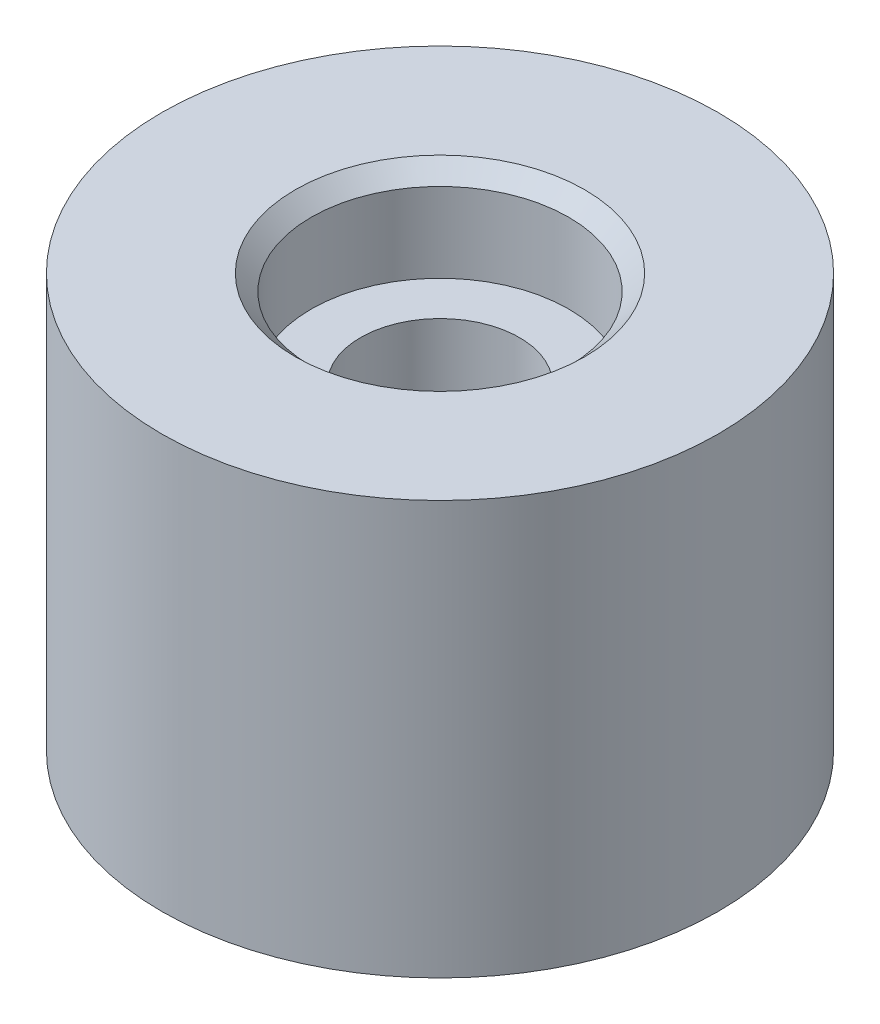
SolidWorks part; units mm, degrees
ref_plane "Front" through (0, 0, 0) normal (0, 0, 1) x (1, 0, 0)
ref_plane "Top" through (0, 0, 0) normal (0, 1, 0) x (1, 0, 0)
ref_plane "Right" through (0, 0, 0) normal (1, 0, 0) x (0, 0, -1)
sketch "Sketch1" plane through (0, 0, 0) normal (0, 1, 0) x (1, 0, 0)
  circle A0 centre (0, 0) radius 8.75
  dimension "D1" = 17.5
extrude "Boss-Extrude1" add sketch "Sketch1" along normal blind 13
sketch "Sketch2" plane through (0, 13, 0) normal (0, 1, 0) x (1, 0, 0)
  circle A0 centre (0, 0) radius 2.5
  dimension "D1" = 5
extrude "Cut-Extrude1" cut sketch "Sketch2" against normal up to next
sketch "Sketch3" plane through (0, 13, 0) normal (0, 1, 0) x (1, 0, 0)
  circle A0 centre (0, 0) radius 4.05
  circle A1 centre (0, 0) radius 2.5 construction
  dimension "D1" = 8.1
extrude "Cut-Extrude2" cut sketch "Sketch3" against normal blind 3
ref_plane "Plane1" through (0, 6.5, 0) normal (0, 1, 0) x (1, 0, 0)
mirror "Mirror3" about plane through (0, 6.5, 0) normal (0, 1, 0) of "Cut-Extrude2"
chamfer "Chamfer1" distance 0.5 angle 45 2 edges at (0, 13, 4.05) (0, 0, 4.05)
